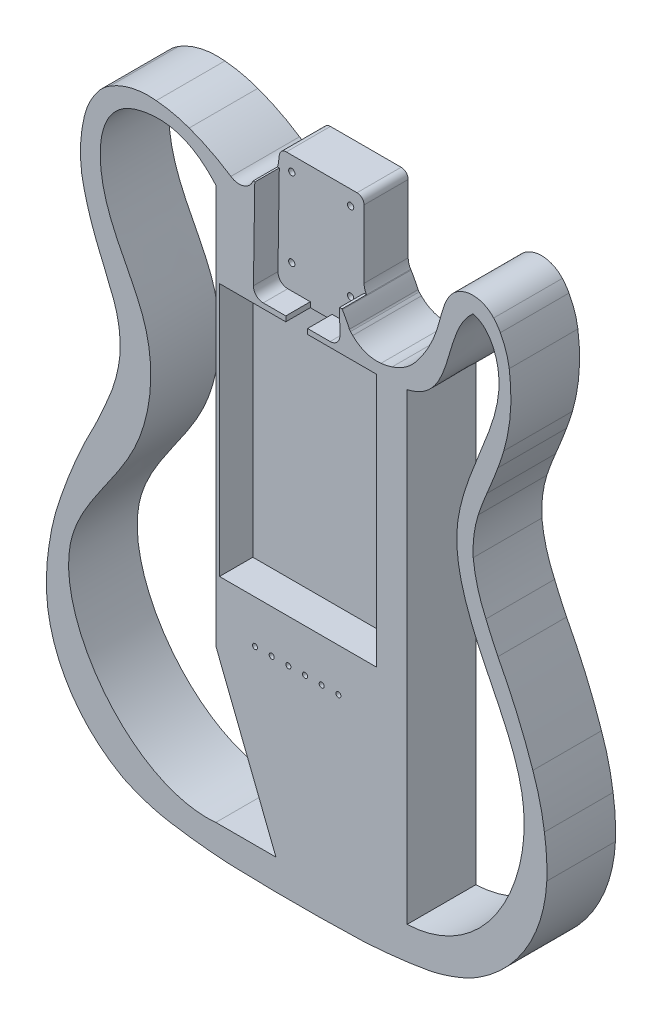
SolidWorks part; units mm, degrees
ref_plane "Front Plane" through (0, 0, 0) normal (0, 0, 1) x (1, 0, 0)
ref_plane "Top Plane" through (0, 0, 0) normal (0, 1, 0) x (1, 0, 0)
ref_plane "Right Plane" through (0, 0, 0) normal (1, 0, 0) x (0, 0, -1)
sketch "Sketch1" plane through (0, 0, 0) normal (0, 0, 1) x (1, 0, 0)
  line L0 (255.3675, -212.0656) -> (264.4462, -212.0656) construction
  line L1 (264.4462, -212.0656) -> (273.5248, -212.0656) construction
  line L2 (254.4921, -211.9425) -> (229.09, -204.656) construction
  line L3 (274.4003, -211.9425) -> (299.8024, -204.656) construction
  line L4 (264.4462, -197.0288) -> (264.4462, -188.6259) construction
  line L5 (292.1992, -149.0184) -> (292.1992, -105.0808)
  line L6 (353.0408, -434.0524) -> (359.3908, -434.0524) construction
  line L7 (354.3108, -292.5744) -> (358.1208, -292.5744) construction
  line L8 (368.9158, -303.3694) -> (368.9158, -424.5274) construction
  line L9 (343.5158, -303.3694) -> (343.5158, -424.5274) construction
  line L10 (231.3871, -188.3166) -> (257.385, -188.3166) construction
  line L11 (271.5074, -188.3166) -> (297.5053, -188.3166) construction
  line L12 (292.2083, -154.6088) -> (292.4425, -170.3149) construction
  line L13 (237.3236, -111.7284) -> (236.4498, -170.3149) construction
  line L14 (261.2712, -222.8223) -> (261.2712, -212.0656) construction
  line L15 (267.6212, -222.5163) -> (267.6212, -212.0656) construction
  line L16 (355.5808, -417.0887) -> (440.1841, -462.3756)
  line L17 (170.139, -116.9111) -> (172.2398, -80.4263) construction
  line L26 (233.0908, -326.0407) -> (228.0254, -311.007) construction
  line L27 (280.249, -340.996) -> (237.8411, -330.4226) construction
  line L28 (286.5004, -339.3572) -> (298.0308, -328.4613) construction
  line L29 (271.5011, -294.9508) -> (296.5271, -311.3952) construction
  line L30 (267.182, -293.874) -> (237.3652, -296.6444) construction
  line L31 (292.2083, -154.6088) -> (293.7952, -154.6089)
  line L32 (237.3236, -111.7284) -> (236.159, -111.7284)
  line L33 (264.4462, -533.3397) -> (264.4462, -35.9424) construction
  line L34 (264.446, -176.7596) -> (264.446, -168.3324) construction
  line L35 (242.7991, -176.7596) -> (257.385, -176.7596) construction
  line L36 (271.5074, -176.7596) -> (286.0933, -176.7596) construction
  line L37 (271.5074, -188.3166) -> (271.5074, -176.7596) construction
  line L38 (257.385, -188.3166) -> (257.385, -176.7596) construction
  line L39 (311.5028, -266.3979) -> (268.9363, -223.8315) construction
  line L40 (302.5225, -275.3781) -> (259.9561, -232.8117) construction
  line L41 (287.6272, -100.5088) -> (241.8598, -100.5088)
  line L42 (236.7013, -109.5293) -> (237.3226, -104.5183)
  line L45 (368.9158, -411.6223) -> (420.0889, -439.0145)
  line L46 (362.6504, -433.4773) -> (409.7247, -458.6755)
  line L47 (300.9797, -323.698) -> (343.5158, -323.698) construction
  line L48 (300.9797, -317.348) -> (343.5158, -317.348) construction
  line L49 (343.5158, -311.8813) -> (308.6561, -277.0216) construction
  line L50 (343.5158, -302.901) -> (313.1462, -272.5315) construction
  arc A0 (298.5861, -163.6364) -> (299.2711, -164.6283) centre (301.4937, -162.3609) ccw
  arc A1 (300.7364, -166.0922) -> (299.2711, -164.6283) centre (222.8934, -242.5472) ccw
  arc A2 (300.7364, -166.0922) -> (319.0259, -172.5122) centre (316.4123, -150.6962) ccw
  arc A3 (319.0259, -172.5122) -> (326.2352, -170.944) centre (314.4164, -133.9661) ccw
  arc A4 (326.2352, -170.944) -> (341.6924, -160.3725) centre (316.2829, -139.806) ccw
  arc A5 (341.6924, -160.3725) -> (356.9315, -129.8398) centre (280.2373, -110.6305) ccw
  arc A6 (360.2177, -118.9602) -> (356.9315, -129.8398) centre (472.2447, -158.7341) ccw
  arc A7 (363.6913, -112.2691) -> (360.2177, -118.9602) centre (386.4375, -128.3247) ccw
  arc A8 (392.0008, -110.6336) -> (363.6913, -112.2691) centre (378.4982, -122.7399) ccw
  arc A9 (396.3203, -116.7099) -> (392.0008, -110.6336) centre (367.666, -132.5065) ccw
  arc A10 (402.0691, -133.9701) -> (396.3203, -116.7099) centre (352.5181, -140.8862) ccw
  arc A11 (398.5108, -181.9349) -> (402.0691, -133.9701) centre (289.2584, -149.7157) ccw
  arc A12 (394.7117, -193.3187) -> (398.5108, -181.9349) centre (237.0194, -134.3662) ccw
  arc A13 (387.6043, -211.1738) -> (394.7117, -193.3187) centre (-23.048, -37.3677) ccw
  arc A14 (387.6043, -211.1738) -> (381.9731, -226.053) centre (577.8696, -291.6876) ccw
  circle A15 centre (378.0352, -293.8788) radius 0.889
  arc A33 (368.9158, -303.3694) -> (358.1208, -292.5744) centre (358.1208, -303.3694) ccw construction
  arc A34 (354.3108, -292.5744) -> (343.5158, -303.3694) centre (354.3108, -303.3694) ccw construction
  arc A35 (231.3871, -188.3166) -> (229.09, -204.656) centre (231.3871, -196.6478) ccw construction
  arc A36 (299.8024, -204.656) -> (297.5053, -188.3166) centre (297.5053, -196.6478) ccw construction
  arc A37 (273.5248, -212.0656) -> (274.4003, -211.9425) centre (273.5248, -208.8906) ccw construction
  arc A38 (254.4921, -211.9425) -> (255.3675, -212.0656) centre (255.3675, -208.8906) ccw construction
  circle A39 centre (300.6412, -197.0288) radius 2.3813 construction
  circle A40 centre (228.2512, -197.0288) radius 2.3813 construction
  circle A41 centre (190.7346, -293.8788) radius 0.889
  circle A45 centre (216.6438, -195.7754) radius 0.9906 construction
  circle A46 centre (237.8426, -363.958) radius 0.9906 construction
  arc A47 (369.9797, -491.4239) -> (383.1407, -484.5884) centre (341.6053, -420.7038) ccw
  arc A48 (383.1407, -484.5884) -> (426.3677, -409.2054) centre (331.2197, -404.73) ccw
  circle A49 centre (361.0363, -437.4278) radius 0.9906 construction
  circle A50 centre (375.8404, -153.7439) radius 0.9906
  arc A51 (292.1992, -105.0808) -> (287.6272, -100.5088) centre (287.6272, -105.0808) ccw
  arc A52 (359.3908, -434.0524) -> (368.9158, -424.5274) centre (359.3908, -424.5274) ccw construction
  arc A53 (343.5158, -424.5274) -> (353.0408, -434.0524) centre (353.0408, -424.5274) ccw construction
  circle A55 centre (356.2158, -289.002) radius 0.8255 construction
  circle A56 centre (356.2158, -437.6248) radius 0.8255 construction
  circle A57 centre (264.4462, -249.0804) radius 1.5875 construction
  circle A58 centre (264.4462, -477.6804) radius 1.5875
  arc A59 (286.0933, -176.7596) -> (292.4425, -170.3149) centre (286.0933, -170.4096) ccw construction
  arc A60 (236.4498, -170.3149) -> (242.7991, -176.7596) centre (242.7991, -170.4096) ccw construction
  circle A61 centre (296.8434, -363.9576) radius 1.0795 construction
  circle A62 centre (275.2536, -363.9576) radius 1.0795 construction
  circle A63 centre (253.664, -363.9576) radius 1.0795 construction
  circle A64 centre (232.0734, -363.9576) radius 1.0795 construction
  circle A65 centre (291.4462, -372.0852) radius 1.651 construction
  circle A66 centre (280.6516, -372.0852) radius 1.651 construction
  circle A67 centre (269.8566, -372.0852) radius 1.651 construction
  circle A68 centre (259.061, -372.0852) radius 1.651 construction
  circle A69 centre (248.2654, -372.0852) radius 1.651 construction
  circle A70 centre (237.4714, -372.0852) radius 1.651 construction
  circle A91 centre (378.3902, -122.9872) radius 0.889
  circle A92 centre (324.0598, -293.8788) radius 0.889 construction
  circle A93 centre (228.8868, -140.5904) radius 0.889
  arc A94 (237.3652, -296.6444) -> (228.0254, -311.007) centre (238.3756, -307.5196) ccw construction
  arc A95 (233.0908, -326.0407) -> (237.8411, -330.4226) centre (239.4695, -323.8915) ccw construction
  arc A96 (280.249, -340.996) -> (286.5004, -339.3572) centre (281.8774, -334.465) ccw construction
  arc A97 (298.0308, -328.4613) -> (296.5271, -311.3952) centre (290.5293, -320.523) ccw construction
  arc A98 (271.5011, -294.9508) -> (267.182, -293.874) centre (267.8047, -300.5761) ccw construction
  arc A99 (268.9363, -223.8315) -> (259.9561, -232.8117) centre (264.4462, -228.3216) ccw construction
  arc A100 (302.5225, -275.3781) -> (311.5028, -275.3781) centre (307.0126, -270.888) ccw construction
  arc A101 (311.5028, -275.3781) -> (311.5028, -266.3979) centre (307.0126, -270.888) ccw construction
  circle A102 centre (245.3978, -160.8336) radius 2.032
  circle A103 centre (283.4978, -160.8336) radius 2.032
  circle A104 centre (283.4978, -110.0336) radius 2.032
  circle A105 centre (245.3978, -110.0336) radius 2.032
  arc A106 (241.8598, -100.5088) -> (237.3226, -104.5183) centre (241.8598, -105.0808) ccw
  arc A107 (292.1992, -149.0184) -> (293.7952, -154.6089) centre (302.5829, -149.077) ccw
  arc A108 (293.7952, -154.6089) -> (294.036, -154.9688) centre (302.7937, -148.8489) ccw
  arc A109 (298.5861, -163.6364) -> (294.036, -154.9688) centre (234.5218, -191.7393) ccw
  arc A110 (381.9731, -226.053) -> (378.7456, -251.638) centre (451.614, -247.8341) ccw
  arc A111 (378.7456, -251.638) -> (387.0056, -281.868) centre (473.536, -241.9811) ccw
  arc A112 (387.0056, -281.868) -> (394.746, -299.1376) centre (668.7935, -165.937) ccw
  arc A113 (417.3556, -351.5884) -> (394.746, -299.1376) centre (80.4909, -465.6996) ccw
  arc A114 (424.8464, -382.4484) -> (417.3556, -351.5884) centre (273.7558, -402.7844) ccw
  arc A115 (426.3677, -409.2054) -> (424.8464, -382.4484) centre (286.7086, -403.7238) ccw
  arc A116 (353.3461, -496.801) -> (369.9797, -491.4239) centre (322.6987, -373.581) ccw
  arc A117 (307.8756, -502.3376) -> (349.8373, -497.5433) centre (288.5477, -147.1431) ccw
  arc A118 (221.4182, -502.3513) -> (307.8756, -502.3376) centre (264.4456, 766.9622) ccw
  arc A119 (182.0911, -498.0608) -> (220.5936, -502.3144) centre (240.3434, -147.16) ccw
  arc A120 (155.5294, -490.0098) -> (168.8471, -494.9386) centre (206.2073, -373.5338) ccw
  arc A121 (102.5148, -408.988) -> (150.7976, -487.651) centre (197.6727, -404.73) ccw
  arc A122 (104.046, -382.4484) -> (102.5148, -408.988) centre (242.065, -403.7256) ccw
  arc A123 (111.5356, -351.5884) -> (104.046, -382.4484) centre (255.1378, -402.7788) ccw
  arc A124 (134.1464, -299.1376) -> (111.5356, -351.5884) centre (448.2456, -465.6404) ccw
  arc A125 (134.1464, -299.1376) -> (141.8856, -281.868) centre (-139.905, -165.9555) ccw
  arc A126 (141.8856, -281.868) -> (150.1456, -251.638) centre (55.4068, -241.9953) ccw
  arc A127 (150.1456, -251.638) -> (143.0364, -216.2088) centre (77.3673, -247.8137) ccw
  arc A128 (143.0364, -216.2088) -> (136.806, -200.9676) centre (-189.4378, -343.226) ccw
  arc A129 (129.8252, -181.788) -> (136.806, -200.9676) centre (324.3166, -121.8593) ccw
  arc A130 (125.2556, -162.9888) -> (129.8252, -181.788) centre (275.6939, -136.3761) ccw
  arc A131 (127.036, -129.7188) -> (125.2556, -162.9888) centre (213.3553, -151.0206) ccw
  arc A132 (137.4456, -109.7788) -> (127.036, -129.7188) centre (173.1607, -141.1109) ccw
  arc A133 (143.666, -104.698) -> (137.4456, -109.7788) centre (162.4404, -134.0314) ccw
  arc A134 (173.5156, -97.9688) -> (143.666, -104.698) centre (168.4714, -145.1623) ccw
  arc A135 (194.8464, -102.668) -> (173.5156, -97.9688) centre (166.5725, -180.2475) ccw
  arc A136 (221.848, -116.3068) -> (194.8464, -102.668) centre (151.4563, -222.118) ccw
  arc A137 (221.848, -116.3068) -> (236.7013, -109.5293) centre (227.1904, -108.3501) ccw
  arc A138 (220.5936, -502.3144) -> (221.4182, -502.3513) centre (222.709, -464.2732) ccw
  arc A139 (349.8373, -497.5433) -> (353.3461, -496.801) centre (341.0846, -447.503) ccw
  arc A143 (168.8471, -494.9386) -> (182.0911, -498.0608) centre (198.7298, -397.8325) ccw
  arc A144 (150.7976, -487.651) -> (155.5294, -490.0098) centre (175.7968, -443.4279) ccw
  circle A145 centre (237.4714, -372.0852) radius 4.064 construction
  circle A146 centre (248.2654, -372.0852) radius 4.064 construction
  circle A147 centre (259.061, -372.0852) radius 4.064 construction
  circle A148 centre (269.8566, -372.0852) radius 4.064 construction
  circle A149 centre (280.6516, -372.0852) radius 4.064 construction
  circle A150 centre (291.4462, -372.0852) radius 4.064 construction
  circle A151 centre (237.4714, -372.0852) radius 4.826 construction
  circle A152 centre (248.2654, -372.0852) radius 4.826 construction
  circle A153 centre (259.061, -372.0852) radius 4.826 construction
  circle A154 centre (269.8566, -372.0852) radius 4.826 construction
  circle A155 centre (280.6516, -372.0852) radius 4.826 construction
  circle A156 centre (291.4462, -372.0852) radius 4.826 construction
  circle A157 centre (232.0734, -363.9576) radius 2.032 construction
  circle A158 centre (253.664, -363.9576) radius 2.032 construction
  circle A159 centre (275.2536, -363.9576) radius 2.032 construction
  circle A160 centre (296.8434, -363.9576) radius 2.032 construction
sketch "Sketch2" plane through (0, 0, 0) normal (0, 0, 1) x (1, 0, 0)
  line L0 (236.7013, -109.5293) -> (237.3226, -104.5183) construction
  line L1 (287.6272, -100.5088) -> (241.8598, -100.5088) construction
  line L2 (292.1992, -149.0184) -> (292.1992, -105.0808) construction
  line L3 (236.7013, -109.5293) -> (237.3226, -104.5183)
  line L4 (287.6272, -100.5088) -> (241.8598, -100.5088)
  line L5 (292.1992, -149.0184) -> (292.1992, -105.0808)
  arc A0 (293.7952, -154.6089) -> (294.036, -154.9688) centre (302.7937, -148.8489) ccw construction
  arc A1 (298.5861, -163.6364) -> (294.036, -154.9688) centre (234.5218, -191.7393) ccw construction
  arc A2 (298.5861, -163.6364) -> (299.2711, -164.6283) centre (301.4937, -162.3609) ccw construction
  arc A3 (300.7364, -166.0922) -> (299.2711, -164.6283) centre (222.8934, -242.5472) ccw construction
  arc A4 (300.7364, -166.0922) -> (319.0259, -172.5122) centre (316.4123, -150.6962) ccw construction
  arc A5 (319.0259, -172.5122) -> (326.2352, -170.944) centre (314.4164, -133.9661) ccw construction
  arc A6 (326.2352, -170.944) -> (341.6924, -160.3725) centre (316.2829, -139.806) ccw construction
  arc A7 (341.6924, -160.3725) -> (356.9315, -129.8398) centre (280.2373, -110.6305) ccw construction
  arc A8 (360.2177, -118.9602) -> (356.9315, -129.8398) centre (472.2447, -158.7341) ccw construction
  arc A9 (363.6913, -112.2691) -> (360.2177, -118.9602) centre (386.4375, -128.3247) ccw construction
  arc A10 (392.0008, -110.6336) -> (363.6913, -112.2691) centre (378.4982, -122.7399) ccw construction
  arc A11 (396.3203, -116.7099) -> (392.0008, -110.6336) centre (367.666, -132.5065) ccw construction
  arc A12 (402.0691, -133.9701) -> (396.3203, -116.7099) centre (352.5181, -140.8862) ccw construction
  arc A13 (398.5108, -181.9349) -> (402.0691, -133.9701) centre (289.2584, -149.7157) ccw construction
  arc A14 (394.7117, -193.3187) -> (398.5108, -181.9349) centre (237.0194, -134.3662) ccw construction
  arc A15 (387.6043, -211.1738) -> (394.7117, -193.3187) centre (-23.048, -37.3677) ccw construction
  arc A16 (387.6043, -211.1738) -> (381.9731, -226.053) centre (577.8696, -291.6876) ccw construction
  arc A17 (381.9731, -226.053) -> (378.7456, -251.638) centre (451.614, -247.8341) ccw construction
  arc A18 (378.7456, -251.638) -> (387.0056, -281.868) centre (473.536, -241.9811) ccw construction
  arc A19 (387.0056, -281.868) -> (394.746, -299.1376) centre (668.7935, -165.937) ccw construction
  arc A20 (417.3556, -351.5884) -> (394.746, -299.1376) centre (80.4909, -465.6996) ccw construction
  arc A21 (424.8464, -382.4484) -> (417.3556, -351.5884) centre (273.7558, -402.7844) ccw construction
  arc A22 (426.3677, -409.2054) -> (424.8464, -382.4484) centre (286.7086, -403.7238) ccw construction
  arc A23 (383.1407, -484.5884) -> (426.3677, -409.2054) centre (331.2197, -404.73) ccw construction
  arc A24 (369.9797, -491.4239) -> (383.1407, -484.5884) centre (341.6053, -420.7038) ccw construction
  arc A25 (353.3461, -496.801) -> (369.9797, -491.4239) centre (322.6987, -373.581) ccw construction
  arc A26 (349.8373, -497.5433) -> (353.3461, -496.801) centre (341.0846, -447.503) ccw construction
  arc A27 (307.8756, -502.3376) -> (349.8373, -497.5433) centre (288.5477, -147.1431) ccw construction
  arc A28 (221.4182, -502.3513) -> (307.8756, -502.3376) centre (264.4456, 766.9622) ccw construction
  arc A29 (220.5936, -502.3144) -> (221.4182, -502.3513) centre (222.709, -464.2732) ccw construction
  arc A30 (182.0911, -498.0608) -> (220.5936, -502.3144) centre (240.3434, -147.16) ccw construction
  arc A31 (168.8471, -494.9386) -> (182.0911, -498.0608) centre (198.7298, -397.8325) ccw construction
  arc A32 (155.5294, -490.0098) -> (168.8471, -494.9386) centre (206.2073, -373.5338) ccw construction
  arc A33 (150.7976, -487.651) -> (155.5294, -490.0098) centre (175.7968, -443.4279) ccw construction
  arc A34 (102.5148, -408.988) -> (150.7976, -487.651) centre (197.6727, -404.73) ccw construction
  arc A35 (104.046, -382.4484) -> (102.5148, -408.988) centre (242.065, -403.7256) ccw construction
  arc A36 (111.5356, -351.5884) -> (104.046, -382.4484) centre (255.1378, -402.7788) ccw construction
  arc A37 (134.1464, -299.1376) -> (111.5356, -351.5884) centre (448.2456, -465.6404) ccw construction
  arc A38 (134.1464, -299.1376) -> (141.8856, -281.868) centre (-139.905, -165.9555) ccw construction
  arc A39 (141.8856, -281.868) -> (150.1456, -251.638) centre (55.4068, -241.9953) ccw construction
  arc A40 (150.1456, -251.638) -> (143.0364, -216.2088) centre (77.3673, -247.8137) ccw construction
  arc A41 (143.0364, -216.2088) -> (136.806, -200.9676) centre (-189.4378, -343.226) ccw construction
  arc A42 (129.8252, -181.788) -> (136.806, -200.9676) centre (324.3166, -121.8593) ccw construction
  arc A43 (125.2556, -162.9888) -> (129.8252, -181.788) centre (275.6939, -136.3761) ccw construction
  arc A44 (127.036, -129.7188) -> (125.2556, -162.9888) centre (213.3553, -151.0206) ccw construction
  arc A45 (137.4456, -109.7788) -> (127.036, -129.7188) centre (173.1607, -141.1109) ccw construction
  arc A46 (143.666, -104.698) -> (137.4456, -109.7788) centre (162.4404, -134.0314) ccw construction
  arc A47 (173.5156, -97.9688) -> (143.666, -104.698) centre (168.4714, -145.1623) ccw construction
  arc A48 (194.8464, -102.668) -> (173.5156, -97.9688) centre (166.5725, -180.2475) ccw construction
  arc A49 (221.848, -116.3068) -> (194.8464, -102.668) centre (151.4563, -222.118) ccw construction
  arc A50 (221.848, -116.3068) -> (236.7013, -109.5293) centre (227.1904, -108.3501) ccw construction
  arc A51 (241.8598, -100.5088) -> (237.3226, -104.5183) centre (241.8598, -105.0808) ccw construction
  arc A52 (292.1992, -105.0808) -> (287.6272, -100.5088) centre (287.6272, -105.0808) ccw construction
  arc A53 (292.1992, -149.0184) -> (293.7952, -154.6089) centre (302.5829, -149.077) ccw construction
  arc A54 (293.7952, -154.6089) -> (294.036, -154.9688) centre (302.7937, -148.8489) ccw
  arc A55 (298.5861, -163.6364) -> (294.036, -154.9688) centre (234.5218, -191.7393) ccw
  arc A56 (298.5861, -163.6364) -> (299.2711, -164.6283) centre (301.4937, -162.3609) ccw
  arc A57 (300.7364, -166.0922) -> (299.2711, -164.6283) centre (222.8934, -242.5472) ccw
  arc A58 (300.7364, -166.0922) -> (319.0259, -172.5122) centre (316.4123, -150.6962) ccw
  arc A59 (319.0259, -172.5122) -> (326.2352, -170.944) centre (314.4164, -133.9661) ccw
  arc A60 (326.2352, -170.944) -> (341.6924, -160.3725) centre (316.2829, -139.806) ccw
  arc A61 (341.6924, -160.3725) -> (356.9315, -129.8398) centre (280.2373, -110.6305) ccw
  arc A62 (360.2177, -118.9602) -> (356.9315, -129.8398) centre (472.2447, -158.7341) ccw
  arc A63 (363.6913, -112.2691) -> (360.2177, -118.9602) centre (386.4375, -128.3247) ccw
  arc A64 (392.0008, -110.6336) -> (363.6913, -112.2691) centre (378.4982, -122.7399) ccw
  arc A65 (396.3203, -116.7099) -> (392.0008, -110.6336) centre (367.666, -132.5065) ccw
  arc A66 (402.0691, -133.9701) -> (396.3203, -116.7099) centre (352.5181, -140.8862) ccw
  arc A67 (398.5108, -181.9349) -> (402.0691, -133.9701) centre (289.2584, -149.7157) ccw
  arc A68 (394.7117, -193.3187) -> (398.5108, -181.9349) centre (237.0194, -134.3662) ccw
  arc A69 (387.6043, -211.1738) -> (394.7117, -193.3187) centre (-23.048, -37.3677) ccw
  arc A70 (387.6043, -211.1738) -> (381.9731, -226.053) centre (577.8696, -291.6876) ccw
  arc A71 (381.9731, -226.053) -> (378.7456, -251.638) centre (451.614, -247.8341) ccw
  arc A72 (378.7456, -251.638) -> (387.0056, -281.868) centre (473.536, -241.9811) ccw
  arc A73 (387.0056, -281.868) -> (394.746, -299.1376) centre (668.7935, -165.937) ccw
  arc A74 (417.3556, -351.5884) -> (394.746, -299.1376) centre (80.4909, -465.6996) ccw
  arc A75 (424.8464, -382.4484) -> (417.3556, -351.5884) centre (273.7558, -402.7844) ccw
  arc A76 (426.3677, -409.2054) -> (424.8464, -382.4484) centre (286.7086, -403.7238) ccw
  arc A77 (383.1407, -484.5884) -> (426.3677, -409.2054) centre (331.2197, -404.73) ccw
  arc A78 (369.9797, -491.4239) -> (383.1407, -484.5884) centre (341.6053, -420.7038) ccw
  arc A79 (353.3461, -496.801) -> (369.9797, -491.4239) centre (322.6987, -373.581) ccw
  arc A80 (349.8373, -497.5433) -> (353.3461, -496.801) centre (341.0846, -447.503) ccw
  arc A81 (307.8756, -502.3376) -> (349.8373, -497.5433) centre (288.5477, -147.1431) ccw
  arc A82 (221.4182, -502.3513) -> (307.8756, -502.3376) centre (264.4456, 766.9622) ccw
  arc A83 (220.5936, -502.3144) -> (221.4182, -502.3513) centre (222.709, -464.2732) ccw
  arc A84 (182.0911, -498.0608) -> (220.5936, -502.3144) centre (240.3434, -147.16) ccw
  arc A85 (168.8471, -494.9386) -> (182.0911, -498.0608) centre (198.7298, -397.8325) ccw
  arc A86 (155.5294, -490.0098) -> (168.8471, -494.9386) centre (206.2073, -373.5338) ccw
  arc A87 (150.7976, -487.651) -> (155.5294, -490.0098) centre (175.7968, -443.4279) ccw
  arc A88 (102.5148, -408.988) -> (150.7976, -487.651) centre (197.6727, -404.73) ccw
  arc A89 (104.046, -382.4484) -> (102.5148, -408.988) centre (242.065, -403.7256) ccw
  arc A90 (111.5356, -351.5884) -> (104.046, -382.4484) centre (255.1378, -402.7788) ccw
  arc A91 (134.1464, -299.1376) -> (111.5356, -351.5884) centre (448.2456, -465.6404) ccw
  arc A92 (134.1464, -299.1376) -> (141.8856, -281.868) centre (-139.905, -165.9555) ccw
  arc A93 (141.8856, -281.868) -> (150.1456, -251.638) centre (55.4068, -241.9953) ccw
  arc A94 (150.1456, -251.638) -> (143.0364, -216.2088) centre (77.3673, -247.8137) ccw
  arc A95 (143.0364, -216.2088) -> (136.806, -200.9676) centre (-189.4378, -343.226) ccw
  arc A96 (129.8252, -181.788) -> (136.806, -200.9676) centre (324.3166, -121.8593) ccw
  arc A97 (125.2556, -162.9888) -> (129.8252, -181.788) centre (275.6939, -136.3761) ccw
  arc A98 (127.036, -129.7188) -> (125.2556, -162.9888) centre (213.3553, -151.0206) ccw
  arc A99 (137.4456, -109.7788) -> (127.036, -129.7188) centre (173.1607, -141.1109) ccw
  arc A100 (143.666, -104.698) -> (137.4456, -109.7788) centre (162.4404, -134.0314) ccw
  arc A101 (173.5156, -97.9688) -> (143.666, -104.698) centre (168.4714, -145.1623) ccw
  arc A102 (194.8464, -102.668) -> (173.5156, -97.9688) centre (166.5725, -180.2475) ccw
  arc A103 (221.848, -116.3068) -> (194.8464, -102.668) centre (151.4563, -222.118) ccw
  arc A104 (221.848, -116.3068) -> (236.7013, -109.5293) centre (227.1904, -108.3501) ccw
  arc A105 (241.8598, -100.5088) -> (237.3226, -104.5183) centre (241.8598, -105.0808) ccw
  arc A106 (292.1992, -105.0808) -> (287.6272, -100.5088) centre (287.6272, -105.0808) ccw
  arc A107 (292.1992, -149.0184) -> (293.7952, -154.6089) centre (302.5829, -149.077) ccw
extrude "Extrude1" add sketch "Sketch2" along normal blind 44.45
sketch "Sketch3" plane through (0, 0, 44.45) normal (0, 0, 1) x (1, 0, 0)
  line L0 (292.2083, -154.6088) -> (293.7952, -154.6089) construction
  line L1 (292.2083, -154.6088) -> (292.4425, -170.3149) construction
  line L2 (271.5074, -176.7596) -> (286.0933, -176.7596) construction
  line L3 (242.7991, -176.7596) -> (257.385, -176.7596) construction
  line L4 (237.3236, -111.7284) -> (236.159, -111.7284) construction
  line L5 (237.3236, -111.7284) -> (236.4498, -170.3149) construction
  line L6 (292.2083, -154.6088) -> (293.7952, -154.6089)
  line L7 (292.2083, -154.6088) -> (292.4425, -170.3149)
  line L8 (271.5074, -176.7596) -> (286.0933, -176.7596)
  line L9 (242.7991, -176.7596) -> (257.385, -176.7596)
  line L10 (237.3236, -111.7284) -> (236.159, -111.7284)
  line L11 (237.3236, -111.7284) -> (236.4498, -170.3149)
  line L12 (257.385, -176.7596) -> (271.5074, -176.7596)
  line L13 (292.1992, -149.0184) -> (292.1992, -105.0808) construction
  line L14 (287.6272, -100.5088) -> (241.8598, -100.5088) construction
  line L15 (236.7013, -109.5293) -> (237.3226, -104.5183) construction
  line L16 (292.1992, -149.0184) -> (292.1992, -105.0808)
  line L17 (287.6272, -100.5088) -> (241.8598, -100.5088)
  line L18 (236.7013, -109.5293) -> (237.3226, -104.5183)
  arc A0 (286.0933, -176.7596) -> (292.4425, -170.3149) centre (286.0933, -170.4096) ccw construction
  arc A1 (236.4498, -170.3149) -> (242.7991, -176.7596) centre (242.7991, -170.4096) ccw construction
  arc A2 (286.0933, -176.7596) -> (292.4425, -170.3149) centre (286.0933, -170.4096) ccw
  arc A3 (236.4498, -170.3149) -> (242.7991, -176.7596) centre (242.7991, -170.4096) ccw
  arc A4 (221.848, -116.3068) -> (236.7013, -109.5293) centre (227.1904, -108.3501) ccw construction
  arc A5 (292.1992, -149.0184) -> (293.7952, -154.6089) centre (302.5829, -149.077) ccw construction
  arc A6 (292.1992, -105.0808) -> (287.6272, -100.5088) centre (287.6272, -105.0808) ccw construction
  arc A7 (241.8598, -100.5088) -> (237.3226, -104.5183) centre (241.8598, -105.0808) ccw construction
  arc A8 (236.159, -111.7284) -> (236.7013, -109.5293) centre (227.1904, -108.3501) ccw
  arc A9 (292.1992, -149.0184) -> (293.7952, -154.6089) centre (302.5829, -149.077) ccw
  arc A10 (292.1992, -105.0808) -> (287.6272, -100.5088) centre (287.6272, -105.0808) ccw
  arc A11 (241.8598, -100.5088) -> (237.3226, -104.5183) centre (241.8598, -105.0808) ccw
extrude "Extrude2" cut sketch "Sketch3" against normal blind 15.875
sketch "Sketch4" plane through (0, 0, 28.575) normal (0, 0, 1) x (1, 0, 0)
  circle A0 centre (283.4978, -160.8336) radius 2.032 construction
  circle A1 centre (245.3978, -160.8336) radius 2.032 construction
  circle A2 centre (245.3978, -110.0336) radius 2.032 construction
  circle A3 centre (283.4978, -110.0336) radius 2.032 construction
  circle A4 centre (283.4978, -160.8336) radius 2.032
  circle A5 centre (245.3978, -160.8336) radius 2.032
  circle A6 centre (245.3978, -110.0336) radius 2.032
  circle A7 centre (283.4978, -110.0336) radius 2.032
extrude "Extrude3" cut sketch "Sketch4" against normal through all
sketch "Sketch5" plane through (0, 0, 44.45) normal (0, 0, 1) x (1, 0, 0)
  line L5 (242.7991, -176.7596) -> (286.0933, -176.7596) construction
  line L6 (257.385, -176.7596) -> (271.5074, -176.7596)
  line L7 (257.385, -188.3166) -> (257.385, -176.7596) construction
  line L8 (257.385, -188.3166) -> (257.385, -176.7596)
  line L9 (271.5074, -188.3166) -> (271.5074, -176.7596) construction
  line L10 (271.5074, -188.3166) -> (271.5074, -176.7596)
  line L11 (257.385, -188.3166) -> (271.5074, -188.3166)
extrude "Extrude4" cut sketch "Sketch5" against normal up to surface (15.875 mm away) up to face at (285.5298, -110.0336, 28.575)
sketch "Sketch6" plane through (0, 0, 44.45) normal (0, 0, 1) x (1, 0, 0)
  line L0 (271.5074, -188.3166) -> (257.385, -188.3166) construction
  line L1 (271.5074, -188.3166) -> (257.385, -188.3166)
  line L2 (231.3871, -188.3166) -> (257.385, -188.3166) construction
  line L3 (231.3871, -188.3166) -> (257.385, -188.3166)
  line L4 (254.4921, -211.9425) -> (229.09, -204.656) construction
  line L5 (254.4921, -211.9425) -> (229.09, -204.656)
  line L6 (255.3675, -212.0656) -> (264.4462, -212.0656) construction
  line L7 (255.3675, -212.0656) -> (264.4462, -212.0656)
  line L8 (264.4462, -212.0656) -> (273.5248, -212.0656) construction
  line L9 (264.4462, -212.0656) -> (273.5248, -212.0656)
  line L10 (274.4003, -211.9425) -> (299.8024, -204.656) construction
  line L11 (274.4003, -211.9425) -> (299.8024, -204.656)
  line L12 (271.5074, -188.3166) -> (297.5053, -188.3166) construction
  line L13 (271.5074, -188.3166) -> (297.5053, -188.3166)
  arc A0 (231.3871, -188.3166) -> (229.09, -204.656) centre (231.3871, -196.6478) ccw construction
  arc A1 (231.3871, -188.3166) -> (229.09, -204.656) centre (231.3871, -196.6478) ccw
  arc A2 (254.4921, -211.9425) -> (255.3675, -212.0656) centre (255.3675, -208.8906) ccw construction
  arc A3 (254.4921, -211.9425) -> (255.3675, -212.0656) centre (255.3675, -208.8906) ccw
  arc A4 (273.5248, -212.0656) -> (274.4003, -211.9425) centre (273.5248, -208.8906) ccw construction
  arc A5 (273.5248, -212.0656) -> (274.4003, -211.9425) centre (273.5248, -208.8906) ccw
  arc A6 (299.8024, -204.656) -> (297.5053, -188.3166) centre (297.5053, -196.6478) ccw construction
  arc A7 (299.8024, -204.656) -> (297.5053, -188.3166) centre (297.5053, -196.6478) ccw
extrude "Extrude5" cut sketch "Sketch6" against normal blind 17.4498
sketch "Sketch7" plane through (0, 0, 44.45) normal (0, 0, 1) x (1, 0, 0)
  line L0 (267.182, -293.874) -> (237.3652, -296.6444) construction
  line L1 (267.182, -293.874) -> (237.3652, -296.6444)
  line L2 (233.0908, -326.0407) -> (228.0254, -311.007) construction
  line L3 (233.0908, -326.0407) -> (228.0254, -311.007)
  line L4 (271.5011, -294.9508) -> (296.5271, -311.3952) construction
  line L5 (286.5004, -339.3572) -> (298.0308, -328.4613) construction
  line L6 (280.249, -340.996) -> (237.8411, -330.4226) construction
  line L7 (271.5011, -294.9508) -> (296.5271, -311.3952)
  line L8 (286.5004, -339.3572) -> (298.0308, -328.4613)
  line L9 (280.249, -340.996) -> (237.8411, -330.4226)
  arc A0 (237.3652, -296.6444) -> (228.0254, -311.007) centre (238.3756, -307.5196) ccw construction
  arc A1 (237.3652, -296.6444) -> (228.0254, -311.007) centre (238.3756, -307.5196) ccw
  arc A2 (271.5011, -294.9508) -> (267.182, -293.874) centre (267.8047, -300.5761) ccw construction
  arc A3 (298.0308, -328.4613) -> (296.5271, -311.3952) centre (290.5293, -320.523) ccw construction
  arc A4 (280.249, -340.996) -> (286.5004, -339.3572) centre (281.8774, -334.465) ccw construction
  arc A5 (233.0908, -326.0407) -> (237.8411, -330.4226) centre (239.4695, -323.8915) ccw construction
  arc A6 (271.5011, -294.9508) -> (267.182, -293.874) centre (267.8047, -300.5761) ccw
  arc A7 (298.0308, -328.4613) -> (296.5271, -311.3952) centre (290.5293, -320.523) ccw
  arc A8 (280.249, -340.996) -> (286.5004, -339.3572) centre (281.8774, -334.465) ccw
  arc A9 (233.0908, -326.0407) -> (237.8411, -330.4226) centre (239.4695, -323.8915) ccw
extrude "Extrude6" cut sketch "Sketch7" against normal blind 21.59
ref_plane "Plane2" through (440.1841, -462.3756, 0) normal (0.8816, -0.4719, 0) x (0, 0, -1)
fillet "Fillet3" [suppressed] radius 3.175
fillet "Fillet10" [suppressed] radius 3.175
fillet "Fillet11" [suppressed] radius 3.175
sketch "Sketch11" plane through (0, 0, 44.45) normal (0, 0, 1) x (1, 0, 0)
  line L0 (311.5028, -266.3979) -> (268.9363, -223.8315) construction
  line L1 (311.5028, -266.3979) -> (268.9363, -223.8315)
  line L2 (302.5225, -275.3781) -> (259.9561, -232.8117) construction
  line L3 (302.5225, -275.3781) -> (259.9561, -232.8117)
  arc A0 (268.9363, -223.8315) -> (259.9561, -232.8117) centre (264.4462, -228.3216) ccw construction
  arc A1 (268.9363, -223.8315) -> (259.9561, -232.8117) centre (264.4462, -228.3216) ccw
  arc A2 (302.5225, -275.3781) -> (311.5028, -275.3781) centre (307.0126, -270.888) ccw construction
  arc A3 (302.5225, -275.3781) -> (311.5028, -275.3781) centre (307.0126, -270.888) ccw
  arc A4 (311.5028, -275.3781) -> (311.5028, -266.3979) centre (307.0126, -270.888) ccw construction
  arc A5 (311.5028, -275.3781) -> (311.5028, -266.3979) centre (307.0126, -270.888) ccw
extrude "Extrude9" cut sketch "Sketch11" against normal blind 17.4498
sketch "Sketch12" plane through (0, 0, 44.45) normal (0, 0, 1) x (1, 0, 0)
  circle A0 centre (291.4462, -372.0852) radius 1.651 construction
  circle A1 centre (280.6516, -372.0852) radius 1.651 construction
  circle A2 centre (269.8566, -372.0852) radius 1.651 construction
  circle A3 centre (259.061, -372.0852) radius 1.651 construction
  circle A4 centre (248.2654, -372.0852) radius 1.651 construction
  circle A5 centre (237.4714, -372.0852) radius 1.651 construction
  circle A6 centre (291.4462, -372.0852) radius 1.651
  circle A7 centre (280.6516, -372.0852) radius 1.651
  circle A8 centre (269.8566, -372.0852) radius 1.651
  circle A9 centre (259.061, -372.0852) radius 1.651
  circle A10 centre (248.2654, -372.0852) radius 1.651
  circle A11 centre (237.4714, -372.0852) radius 1.651
extrude "Extrude10" cut sketch "Sketch12" against normal through all
sketch "Sketch13" plane through (0, 0, 0) normal (0, 0, -1) x (-1, 0, 0)
  circle A0 centre (-291.4462, -372.0852) radius 4.826 construction
  circle A1 centre (-291.4462, -372.0852) radius 4.826
  circle A2 centre (-280.6516, -372.0852) radius 4.826 construction
  circle A3 centre (-280.6516, -372.0852) radius 4.826
  circle A4 centre (-269.8566, -372.0852) radius 4.826 construction
  circle A5 centre (-269.8566, -372.0852) radius 4.826
  circle A6 centre (-259.061, -372.0852) radius 4.826 construction
  circle A7 centre (-259.061, -372.0852) radius 4.826
  circle A8 centre (-248.2654, -372.0852) radius 4.826 construction
  circle A9 centre (-248.2654, -372.0852) radius 4.826
  circle A10 centre (-237.4714, -372.0852) radius 4.826 construction
  circle A11 centre (-237.4714, -372.0852) radius 4.826
extrude "Extrude11" cut sketch "Sketch13" against normal blind 1.4224
sketch "Sketch14" plane through (0, 0, 0) normal (0, 0, -1) x (-1, 0, 0)
  circle A0 centre (-291.4462, -372.0852) radius 4.064 construction
  circle A1 centre (-291.4462, -372.0852) radius 4.064
  circle A2 centre (-280.6516, -372.0852) radius 4.064 construction
  circle A3 centre (-280.6516, -372.0852) radius 4.064
  circle A4 centre (-269.8566, -372.0852) radius 4.064 construction
  circle A5 centre (-269.8566, -372.0852) radius 4.064
  circle A6 centre (-259.061, -372.0852) radius 4.064 construction
  circle A7 centre (-259.061, -372.0852) radius 4.064
  circle A8 centre (-248.2654, -372.0852) radius 4.064 construction
  circle A9 centre (-248.2654, -372.0852) radius 4.064
  circle A10 centre (-237.4714, -372.0852) radius 4.064 construction
  circle A11 centre (-237.4714, -372.0852) radius 4.064
extrude "Extrude12" cut sketch "Sketch14" against normal blind 7.874
sketch "Sketch15" plane through (0, 0, 44.45) normal (0, 0, 1) x (1, 0, 0)
  line L0 (260.712, -372.0852) -> (269.8566, -372.0852)
  line L1 (214.4843, -180.0871) -> (316.0843, -180.0871)
  line L2 (214.4843, -180.0871) -> (214.4843, -344.3212)
  line L3 (214.4843, -344.3212) -> (316.0843, -344.3212)
  line L4 (316.0843, -180.0871) -> (316.0843, -344.3212)
  line L5 (265.2843, -372.0852) -> (265.2843, -365.3932)
  circle A0 centre (259.061, -372.0852) radius 1.651 construction
  dimension "D1" = 101.6
  dimension "D2" = 50.8
extrude "Cut-Extrude1" cut sketch "Sketch15" against normal up to surface (21.59 mm away) contours L4 L1 L2 L3 up to face at (263.6708, -317.1564, 22.86)
sketch "Sketch16" plane through (0, 0, 44.45) normal (0, 0, 1) x (1, 0, 0)
  line L0 (212.1177, -126.053) -> (212.1177, -483.3989)
  spline S0 degree 3 poles (159.7707, -109.6975) (135.6958, -117.2236) (132.5366, -173.1445) (175.5739, -226.4644) (166.8372, -308.2444) (79.9546, -386.3658) (159.4423, -488.5151) (212.1177, -483.3989) knots 0 0 0 0 0.149043 0.296709 0.455651 0.647251 1 1 1 1
  spline S1 degree 2 poles (159.7707, -109.6975) (189.9103, -100.6718) (212.1177, -126.053) knots 0 0 0 1 1 1
extrude "Cut-Extrude2" cut sketch "Sketch16" against normal blind 127
sketch "Sketch17" plane through (0, 0, 44.45) normal (0, 0, 1) x (1, 0, 0)
  line L0 (335.9446, -178.7913) -> (335.9446, -478.6679)
  spline S0 degree 3 poles (378.5972, -114.9931) (357.9748, -133.1978) (367.973, -171.5097) (335.9446, -178.7913) knots 0 0 0 0 1 1 1 1
  spline S1 degree 3 poles (378.5972, -114.9931) (386.104, -116.7157) (401.9416, -140.9828) (384.7332, -188.653) (361.8409, -239.7961) (381.0223, -305.9861) (435.3162, -384.0785) (386.6346, -476.3469) (335.9446, -478.6679) knots 0 0 0 0 0.053147 0.186284 0.336553 0.449658 0.663661 1 1 1 1
extrude "Cut-Extrude3" cut sketch "Sketch17" against normal blind 127
sketch "Sketch18" plane through (0, 0, 44.45) normal (0, 0, 1) x (1, 0, 0)
  line L0 (212.1177, -384.507) -> (251.0341, -483.3989)
  line L1 (212.1177, -483.3989) -> (212.1177, -126.053) construction
  line L2 (251.0341, -483.3989) -> (212.1177, -483.3989)
  line L3 (212.1177, -483.3989) -> (212.1177, -384.507)
extrude "Cut-Extrude4" cut sketch "Sketch18" against normal blind 76.2
